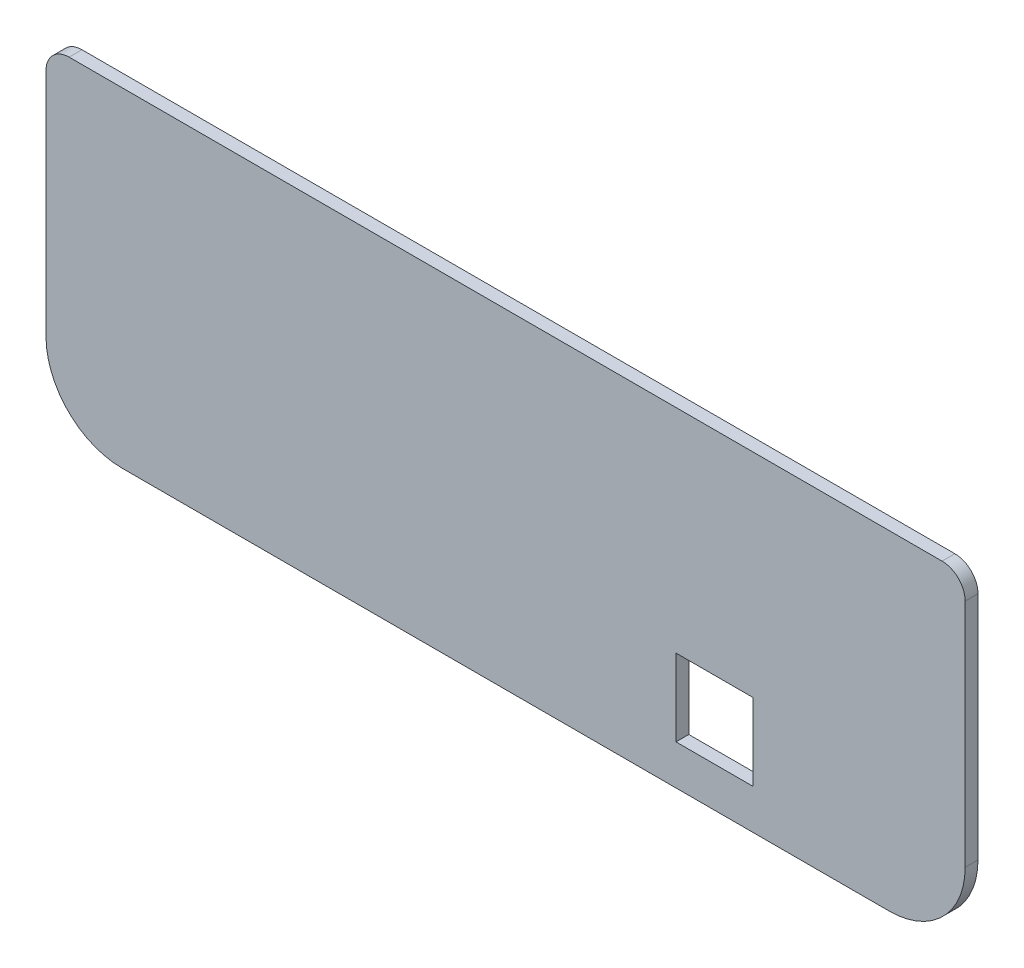
SolidWorks part; units mm, degrees
ref_plane "Plan de face" through (0, 0, 0) normal (0, 0, 1) x (1, 0, 0)
ref_plane "Plan de dessus" through (0, 0, 0) normal (0, 1, 0) x (1, 0, 0)
ref_plane "Plan de droite" through (0, 0, 0) normal (1, 0, 0) x (0, 0, -1)
sketch "Esquisse20" plane through (0, 0, 0) normal (0, 0, 1) x (1, 0, 0)
  line L1 (14.8, -2) -> (164.37, -2)
  line L2 (0, 12.8) -> (0, 57.73)
  line L3 (4.5, 62.23) -> (174.67, 62.23)
  line L4 (179.17, 12.8) -> (179.17, 57.73)
  arc A0 (0, 57.73) -> (4.5, 62.23) centre (4.5, 57.73) cw
  arc A1 (174.67, 62.23) -> (179.17, 57.73) centre (174.67, 57.73) cw
  arc A2 (164.37, -2) -> (179.17, 12.8) centre (164.37, 12.8) ccw
  arc A3 (14.8, -2) -> (0, 12.8) centre (14.8, 12.8) cw
  point P7 (0, 62.23)
  point P10 (179.17, 62.23)
  point P14 (179.17, -2)
  point P17 (0, -2)
extrude "Boss.-Extru.1" add sketch "Esquisse20" along normal blind 2.5
sketch "Esquisse21" plane through (0, 0, 0) normal (0, 0, -1) x (-1, 0, 0)
  line L1 (-137.7949, 5.7802) -> (-122.7949, 5.7802)
  line L2 (-137.7949, 5.7802) -> (-137.7949, 20.7802)
  line L3 (-137.7949, 20.7802) -> (-122.7949, 20.7802)
  line L4 (-122.7949, 5.7802) -> (-122.7949, 20.7802)
  dimension "D1" = 15
  dimension "D2" = 15
extrude "Enlèv. mat.-Extru.1" cut sketch "Esquisse21" against normal blind 10
